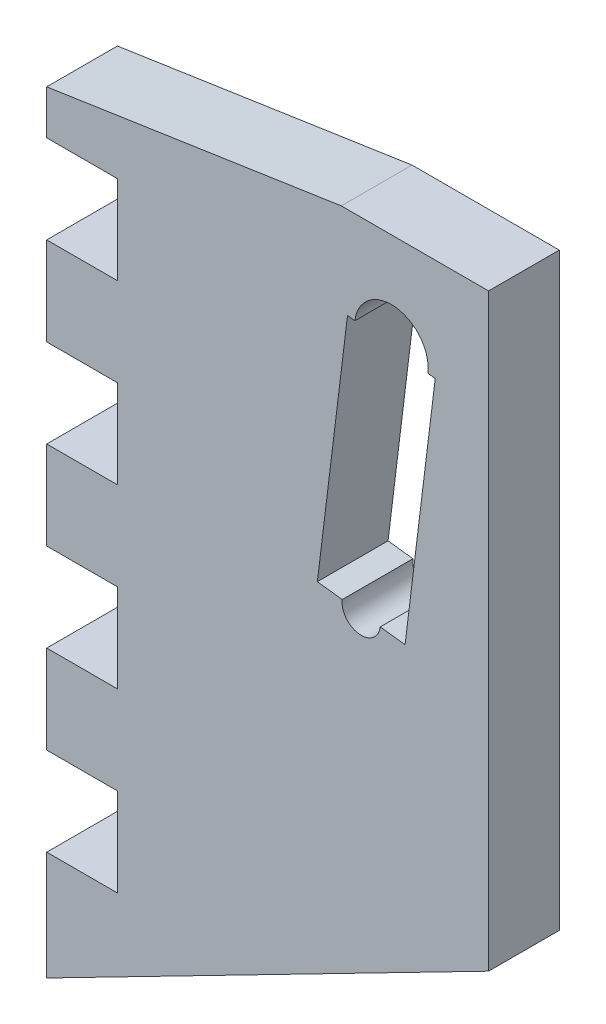
SolidWorks part; units mm, degrees
material "Thornel VCB-20 Carbon Cloth"
ref_plane "Front Plane" through (0, 0, 0) normal (0, 0, 1) x (1, 0, 0)
ref_plane "Top Plane" through (0, 0, 0) normal (0, 1, 0) x (1, 0, 0)
ref_plane "Right Plane" through (0, 0, 0) normal (1, 0, 0) x (0, 0, -1)
sketch "Sketch1" plane through (0, 0, 0) normal (0, 0, 1) x (1, 0, 0)
  line L0 (0, 0) -> (-38.1, 0)
  line L1 (0, 0) -> (0, -50.8)
  line L2 (-38.1, 0) -> (-38.1, -7.62)
  line L3 (-38.1, -7.62) -> (-32.004, -7.62)
  line L4 (-32.004, -7.62) -> (-32.004, -15.24)
  line L5 (-32.004, -15.24) -> (-38.1, -15.24)
  line L6 (-38.1, -45.72) -> (-38.1, -70.358)
  line L7 (-38.1, -15.24) -> (-38.1, -22.86)
  line L8 (-38.1, -22.86) -> (-32.004, -22.86)
  line L9 (-32.004, -22.86) -> (-32.004, -30.48)
  line L10 (-32.004, -30.48) -> (-38.1, -30.48)
  line L11 (-38.1, -30.48) -> (-38.1, -38.1)
  line L12 (-38.1, -38.1) -> (-32.004, -38.1)
  line L13 (-32.004, -38.1) -> (-32.004, -45.72)
  line L14 (-32.004, -45.72) -> (-38.1, -45.72)
  line L15 (-38.1, -70.358) -> (0, -50.8)
  circle A0 centre (-8.382, -8.382) radius 3.175
  dimension "D9" = 6.35
  dimension "D1" = 38.1
  dimension "D2" = 50.8
  dimension "D3" = 7.62
  dimension "D4" = 7.62
  dimension "D6" = 6.096
  dimension "D8" = 70.358
  dimension "D12" = 8.382
  dimension "D13" = 8.382
  dimension "D7" = 3
extrude "Boss-Extrude1" add sketch "Sketch1" along normal blind 6.096
sketch "Sketch2" plane through (0, 0, 0) normal (0, 0, -1) x (-1, 0, 0)
  line L5 (38.1, 0) -> (12.7, 0)
  line L6 (0, 0) -> (38.1, 0) construction
  line L7 (12.7, 0) -> (38.1, -3.81)
  line L8 (38.1, 0) -> (38.1, -7.62) construction
  line L9 (38.1, -3.81) -> (38.1, 0)
  dimension "D1" = 25.4
  dimension "D2" = 3.81
extrude "Cut-Extrude1" cut sketch "Sketch2" against normal blind 8.636
sketch "Sketch4" plane through (0, 0, 6.096) normal (0, 0, 1) x (1, 0, 0)
  line L0 (-38.1, -45.72) -> (-38.1, -53.34)
  line L1 (-38.1, -45.72) -> (-38.1, -70.358) construction
  line L2 (-38.1, -53.34) -> (-32.004, -53.34)
  line L3 (-32.004, -53.34) -> (-32.004, -60.96)
  line L4 (-32.004, -60.96) -> (-38.1, -60.96)
  line L5 (-38.1, -60.96) -> (-38.1, -53.34)
  line M18 (-38.1, -45.72) -> (-38.1, -70.358)
  dimension "D1" = 7.62
  dimension "D2" = 6.096
  dimension "D3" = 6.096
  dimension "D4" = 7.62
extrude "Cut-Extrude2" cut sketch "Sketch4" against normal through all contours L4 L3 L2 M18
sketch "Sketch5" plane through (0, 0, 0) normal (0, 0, -1) x (-1, 0, 0)
  line L0 (8.382, -8.382) -> (10.9822, -29.559) construction
  line L1 (8.382, -8.382) -> (8.382, -39.2411) construction
  circle A0 centre (8.382, -8.382) radius 3.175 construction
  circle A1 centre (10.9822, -29.559) radius 1.651
  dimension "D1" = 21.336
  dimension "D2" = 7
extrude "Cut-Extrude4" cut sketch "Sketch5" against normal up to surface (6.096 mm away) up to face at (-5.207, -8.382, 6.096)
sketch "Sketch6" plane through (0, 0, 6.096) normal (0, 0, 1) x (1, 0, 0)
  line L0 (-5.2307, -8.7689) -> (-4.6004, -8.8463)
  line L1 (-11.5333, -7.9951) -> (-12.1636, -7.9177)
  line L6 (-14.7638, -29.0946) -> (-12.6209, -29.3578)
  line L7 (-4.6004, -8.8463) -> (-7.2006, -30.0233)
  line L8 (-12.1636, -7.9177) -> (-14.7638, -29.0946)
  line L10 (-9.3435, -29.7602) -> (-7.2006, -30.0233)
  line L11 (-12.6209, -29.3578) -> (-9.3435, -29.7602)
  line L12 (-11.5333, -7.9951) -> (-5.2307, -8.7689)
  dimension "D5" = 21.336
  dimension "D2" = 0.635
  dimension "D3" = 0.635
extrude "Cut-Extrude5" cut sketch "Sketch6" against normal up to surface (6.096 mm away) up to face at (-12.6332, -29.559, 0)
